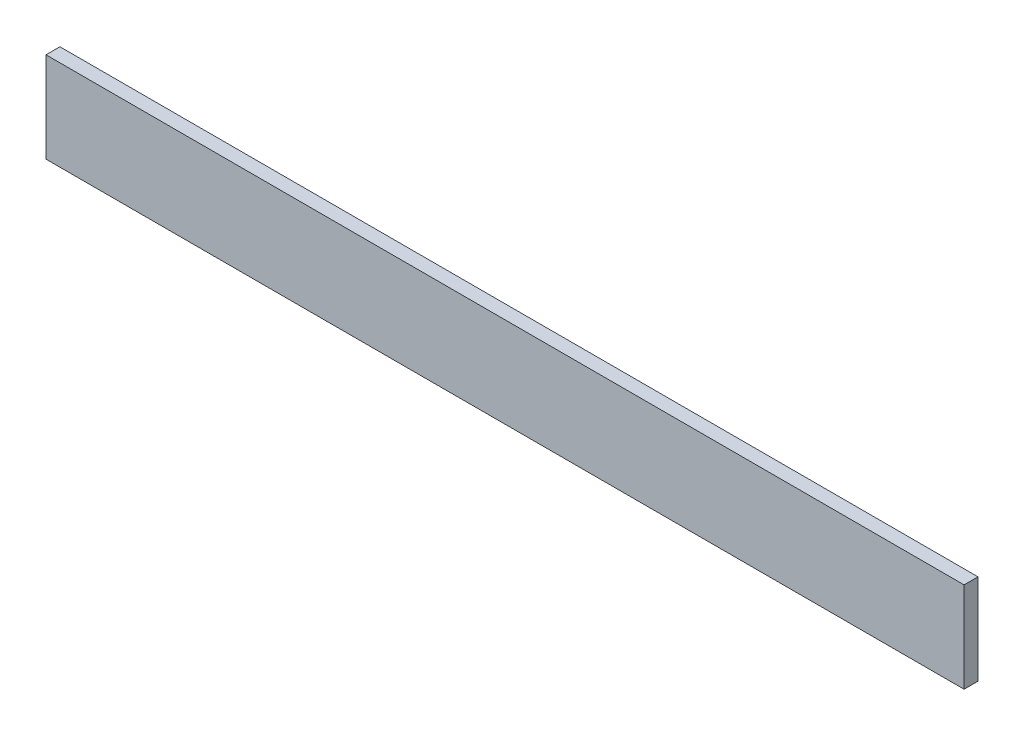
SolidWorks part; units mm, degrees
ref_plane "Alzado" through (0, 0, 0) normal (0, 0, 1) x (1, 0, 0)
ref_plane "Planta" through (0, 0, 0) normal (0, 1, 0) x (1, 0, 0)
ref_plane "Vista lateral" through (0, 0, 0) normal (1, 0, 0) x (0, 0, -1)
sketch "Croquis1" plane through (0, 0, 0) normal (0, 0, 1) x (1, 0, 0)
  line L1 (-660, -65) -> (660, -65)
  line L2 (-660, -65) -> (-660, 65)
  line L3 (-660, 65) -> (660, 65)
  line L4 (660, -65) -> (660, 65)
  line L5 (-660, -65) -> (660, 65) construction
  line L6 (-660, 65) -> (660, -65) construction
  point P0 (0, 0)
  dimension "D1" = 130
  dimension "D2" = 1320
extrude "Saliente-Extruir1" add sketch "Croquis1" along normal blind 20
